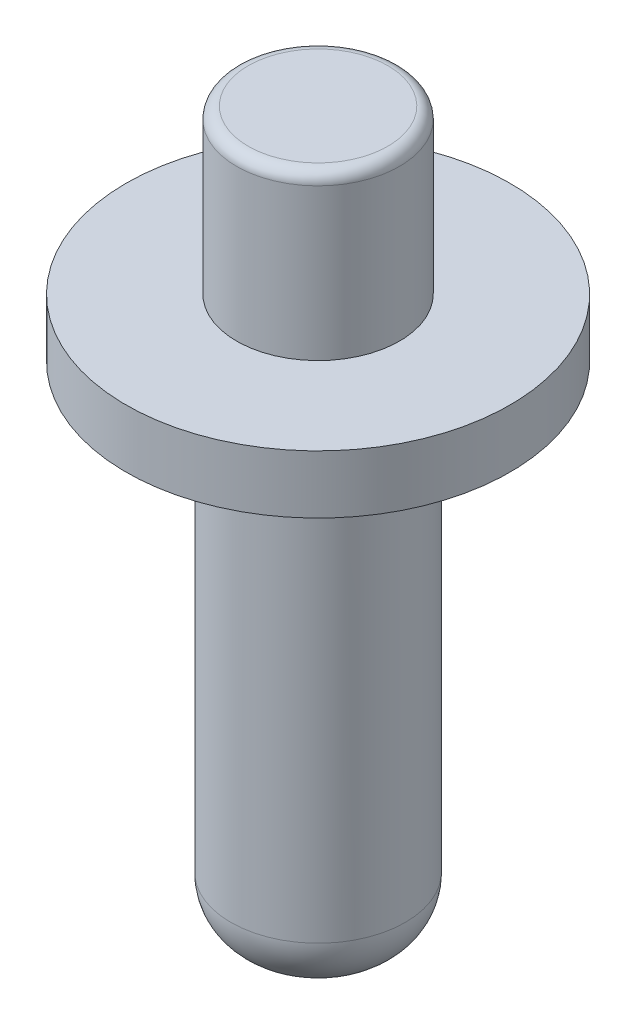
SolidWorks part; units mm, degrees
ref_plane "前视基准面" through (0, 0, 0) normal (0, 0, 1) x (1, 0, 0)
ref_plane "上视基准面" through (0, 0, 0) normal (0, 1, 0) x (1, 0, 0)
ref_plane "右视基准面" through (0, 0, 0) normal (1, 0, 0) x (0, 0, -1)
sketch "草图1" plane through (0, 0, 0) normal (0, 0, 1) x (1, 0, 0)
  line L0 (0, 12.8872) -> (0, -9.0872) construction
  line L1 (0, -4.3) -> (-0.75, -4.3)
  line L2 (-0.75, -4.3) -> (-0.75, 0)
  line L3 (-0.75, 0) -> (-1.65, 0)
  line L4 (-1.65, 0) -> (-1.65, 0.5)
  line L5 (-1.65, 0.5) -> (-0.7, 0.5)
  line L6 (-0.7, 0.5) -> (-0.7, 1.9)
  line L7 (-0.7, 1.9) -> (0, 1.9)
  line L8 (0, -4.3) -> (0, 1.9)
  line L12 (5.0295, 0) -> (-9.301, 0) construction
  point P23 (-1.65, 0.25)
  dimension "D1" = 6.2
  dimension "D2" = 0.5
  dimension "D3" = 0.7
  dimension "D4" = 1.4
  dimension "D5" = 0.75
  dimension "D6" = 1.65
revolve "旋转1" add sketch "草图1" angle 360 about L0
fillet "圆角1" radius 0.1 1 edges at (-0.7, 1.9, 0)
fillet "圆角2" radius 0.5 1 edges at (-0.75, -4.3, 0)
